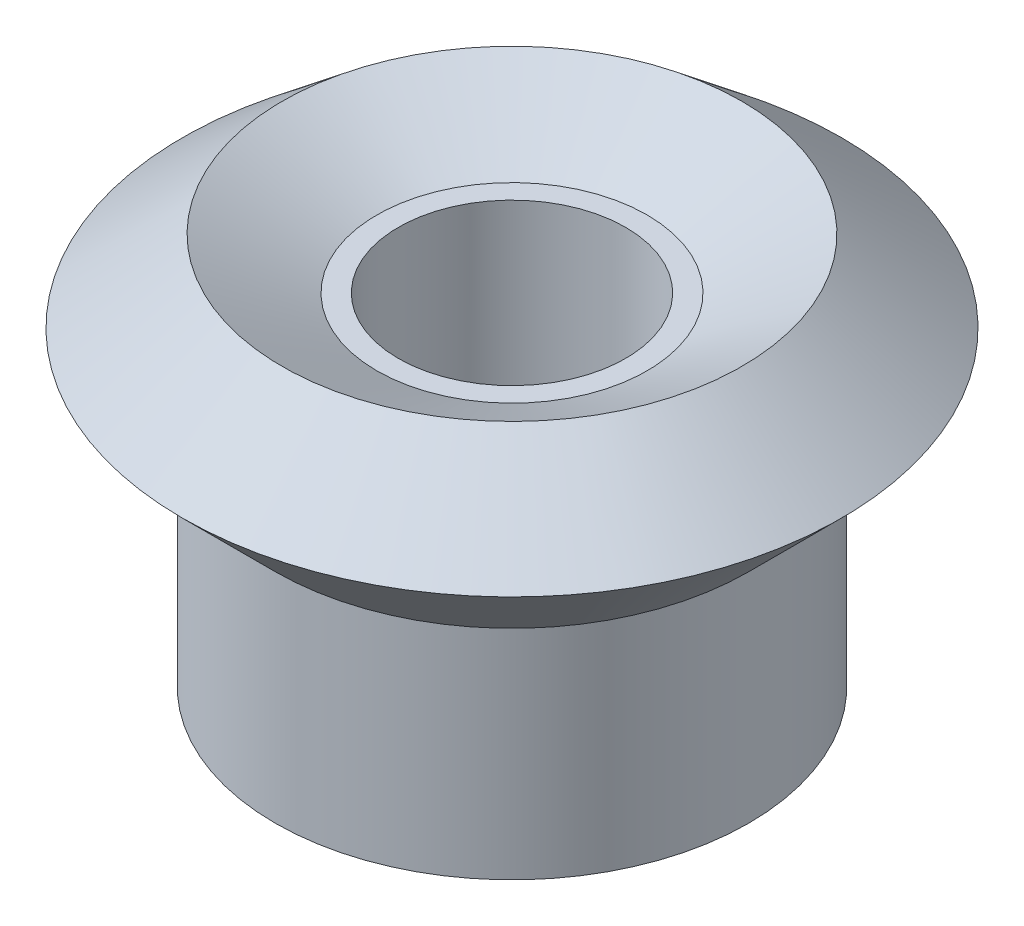
SolidWorks part; units mm, degrees
ref_plane "Front Plane" through (0, 0, 0) normal (0, 0, 1) x (1, 0, 0)
ref_plane "Top Plane" through (0, 0, 0) normal (0, 1, 0) x (1, 0, 0)
ref_plane "Right Plane" through (0, 0, 0) normal (1, 0, 0) x (0, 0, -1)
sketch "Sketch1" plane through (0, 0, 0) normal (0, 0, 1) x (1, 0, 0)
  line L0 (17.4, 16.4) -> (12.1322, 20.7)
  line L1 (12.1322, 20.7) -> (7.1322, 18)
  line L2 (7.1322, 18) -> (5, 18)
  line L3 (5, 18) -> (5, 0)
  line L4 (5, 0) -> (12.5, 0)
  line L5 (12.5, 0) -> (12.5, 11.5)
  line L6 (12.5, 11.5) -> (17.4, 16.4)
  line L7 (0, 20.7) -> (0, 0) construction
revolve "Revolve1" add sketch "Sketch1" angle 360 about L7
sketch "Sketch2" plane through (0, 0, 0) normal (0, -1, 0) x (1, 0, 0)
  circle A0 centre (0, 0) radius 6
  dimension "D1" = 12
extrude "Cut-Extrude1" cut sketch "Sketch2" against normal through all
